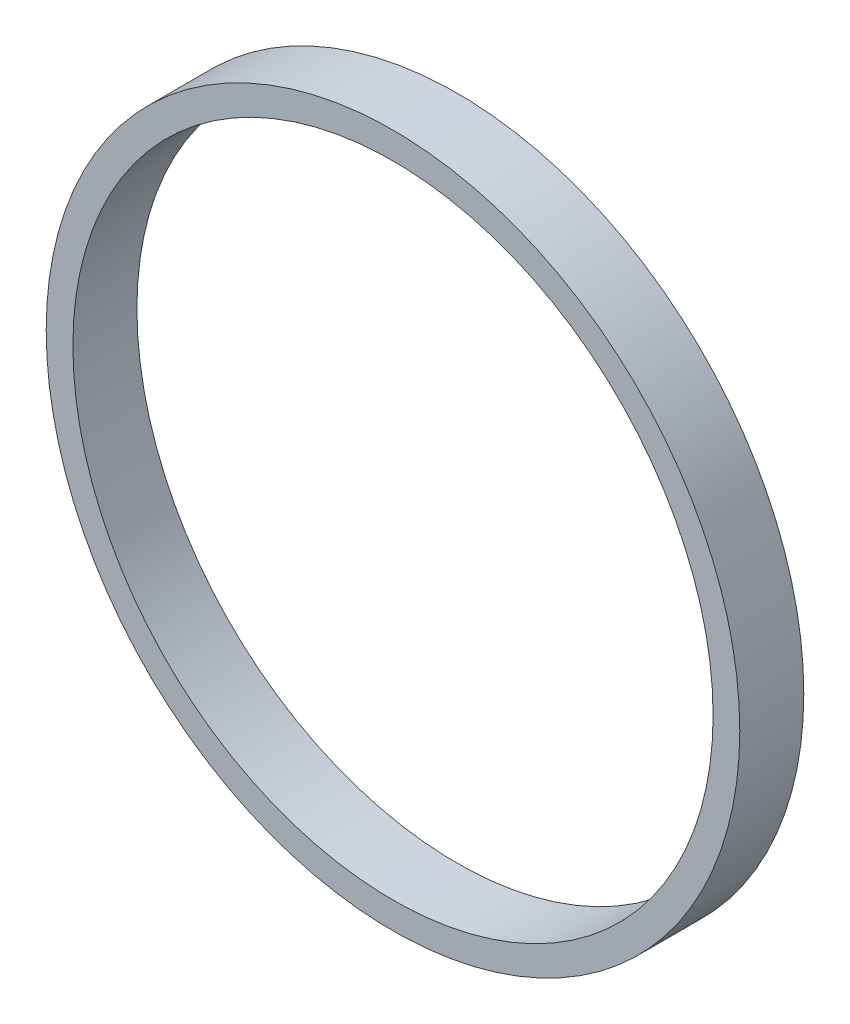
SolidWorks part; units mm, degrees
ref_plane "Front Plane" through (0, 0, 0) normal (0, 0, 1) x (1, 0, 0)
ref_plane "Top Plane" through (0, 0, 0) normal (0, 1, 0) x (1, 0, 0)
ref_plane "Right Plane" through (0, 0, 0) normal (1, 0, 0) x (0, 0, -1)
sketch "Sketch1" plane through (0, 0, 0) normal (0, 0, 1) x (1, 0, 0)
  circle A0 centre (0, 0) radius 32.5
  circle A1 centre (0, 0) radius 30
extrude "Boss-Extrude1" add sketch "Sketch1" along normal blind 6 contours A1 | A0
